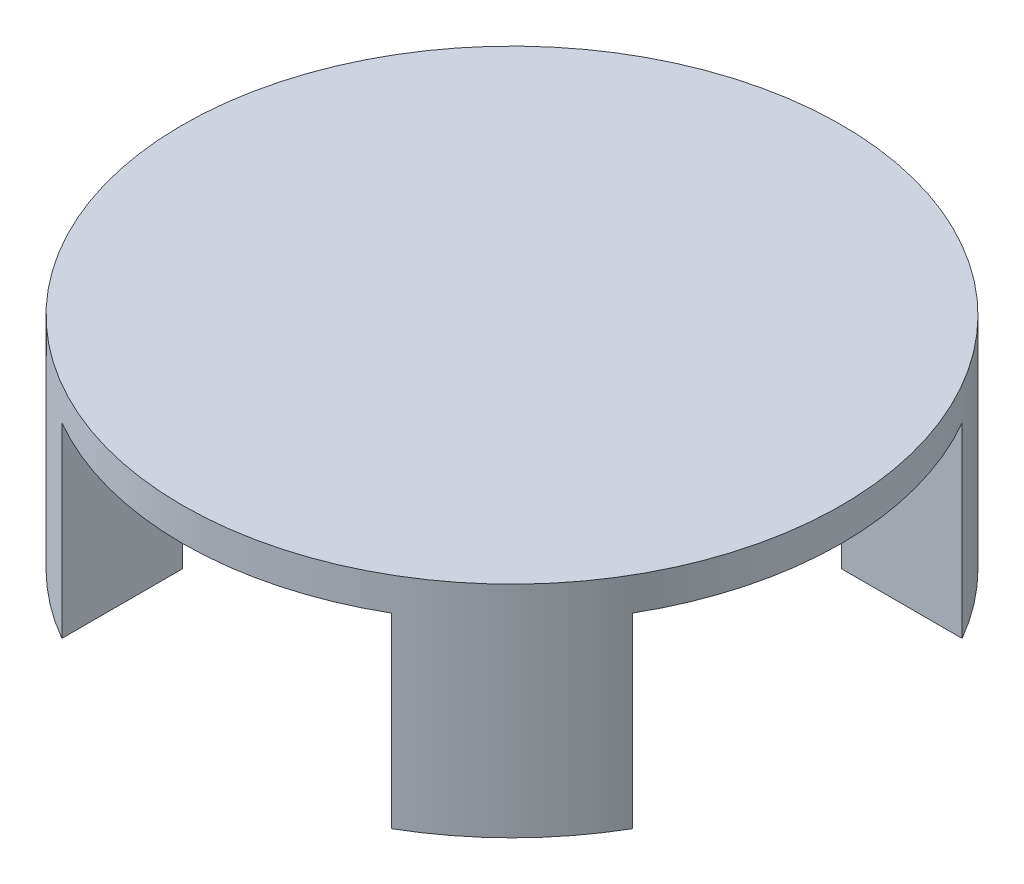
SolidWorks part; units mm, degrees
ref_plane "Alzado" through (0, 0, 0) normal (0, 0, 1) x (1, 0, 0)
ref_plane "Planta" through (0, 0, 0) normal (0, 1, 0) x (1, 0, 0)
ref_plane "Vista lateral" through (0, 0, 0) normal (1, 0, 0) x (0, 0, -1)
sketch "Croquis1" plane through (0, 0, 0) normal (0, 1, 0) x (1, 0, 0)
  circle A0 centre (0, 0) radius 30
  dimension "D1" = 60
extrude "Saliente-Extruir1" add sketch "Croquis1" along normal blind 20
sketch "Croquis2" plane through (0, 0, 0) normal (0, 0, 1) x (1, 0, 0)
  line L0 (-15, 17) -> (-15, 0)
  line L2 (-30, 0) -> (30, 0) construction
  line L3 (0, -14.4183) -> (0, 30.4605) construction
  line L4 (15, 17) -> (15, 0)
  line L5 (30, 20) -> (-30, 20) construction
  line L6 (-15, 17) -> (15, 17)
  line L7 (15, 0) -> (-15, 0)
  dimension "D1" = 15
  dimension "D2" = 3
extrude "Cortar-Extruir1" cut sketch "Croquis2" against normal through all both and the other way through all
sketch "Croquis3" plane through (0, 0, 0) normal (1, 0, 0) x (0, 0, -1)
  line L0 (-15, 17) -> (-15, 0)
  line L3 (0, -14.4183) -> (0, 30.4605) construction
  line L4 (15, 17) -> (15, 0)
  line L6 (-15, 17) -> (15, 17)
  line L7 (15, 0) -> (-15, 0)
  dimension "D1" = 15
extrude "Cortar-Extruir2" cut sketch "Croquis3" against normal through all both and the other way through all
